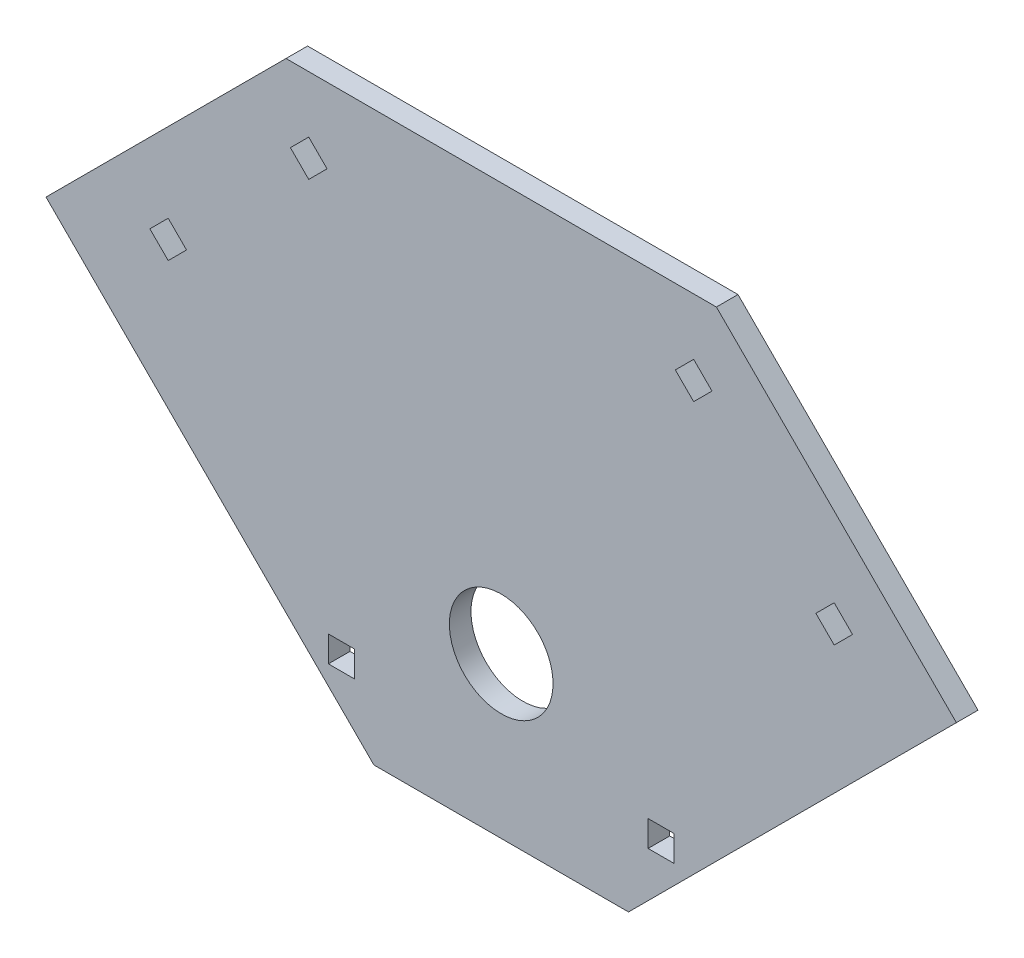
SolidWorks part; units mm, degrees
material "ABS"
ref_plane "Front Plane" through (0, 0, 0) normal (0, 0, 1) x (1, 0, 0)
ref_plane "Top Plane" through (0, 0, 0) normal (0, 1, 0) x (1, 0, 0)
ref_plane "Right Plane" through (0, 0, 0) normal (1, 0, 0) x (0, 0, -1)
sketch "Sketch3" plane through (0, 0, 0) normal (0, 0, 1) x (1, 0, 0)
  line L8 (0, 0) -> (136.4293, 136.4293) construction
  line L9 (0, 0) -> (0, 136.4293) construction
  line L10 (0, 0) -> (-136.4293, 136.4293) construction
  line L20 (-15.2843, -13) -> (15.2843, -13) construction
  line L23 (-15.2843, -13) -> (-77.7817, 49.4975) construction
  line L25 (15.2843, -13) -> (77.7817, 49.4975) construction
  line L27 (-77.7817, 49.4975) -> (-49.4975, 77.7817)
  line L29 (49.4975, 77.7817) -> (77.7817, 49.4975)
  line L32 (-15.2843, -13) -> (15.2843, -13) construction
  line L34 (-27.4975, -22) -> (27.4975, -22)
  line L36 (-27.4975, -22) -> (-88.3883, 38.8909)
  line L37 (-88.3883, 38.8909) -> (-77.7817, 49.4975)
  line L42 (-49.4975, 77.7817) -> (-40.0115, 68.2957) construction
  line L47 (27.4975, -22) -> (88.3883, 38.8909)
  line L48 (88.3883, 38.8909) -> (77.7817, 49.4975)
  line L49 (0, 0) -> (0, -22) construction
  line L50 (-49.4975, 77.7817) -> (-43.8406, 83.4386)
  line L51 (-43.8406, 83.4386) -> (43.8406, 83.4386)
  line L52 (43.8406, 83.4386) -> (49.4975, 77.7817)
  line L53 (49.4975, 77.7817) -> (23.1501, 51.4344) construction
  line L54 (-43.8406, 83.4386) -> (-20.3266, 59.9246) construction
  line L55 (43.8406, 83.4386) -> (35.6049, 75.2028) construction
  line L56 (-81.3173, 44.5477) -> (-77.0746, 48.7904)
  line L57 (-77.0746, 48.7904) -> (-72.832, 44.5477)
  line L58 (-72.832, 44.5477) -> (-77.0746, 40.3051)
  line L59 (-77.0746, 40.3051) -> (-81.3173, 44.5477)
  line L60 (-48.7904, 77.0746) -> (-44.5477, 81.3173)
  line L61 (-44.5477, 81.3173) -> (-40.3051, 77.0746)
  line L62 (-40.3051, 77.0746) -> (-44.5477, 72.832)
  line L63 (-44.5477, 72.832) -> (-48.7904, 77.0746)
  line L64 (40.3051, 77.0746) -> (44.5477, 72.832)
  line L71 (44.5477, 72.832) -> (48.7904, 77.0746)
  line L72 (48.7904, 77.0746) -> (44.5477, 81.3173)
  line L73 (44.5477, 81.3173) -> (40.3051, 77.0746)
  line L74 (72.832, 44.5477) -> (77.0746, 40.3051)
  line L75 (77.0746, 40.3051) -> (81.3173, 44.5477)
  line L76 (81.3173, 44.5477) -> (77.0746, 48.7904)
  line L77 (77.0746, 48.7904) -> (72.832, 44.5477)
  line L82 (0, 0) -> (0, 50) construction
  circle A0 centre (0, 0) radius 12
  point P7 (63.6396, 63.6396)
  point P15 (-63.6396, 63.6396)
  dimension "crankshaftBearingOD" = 24
  dimension "D8" = 45
  dimension "D10" = 45
  dimension "D2" = 90
  dimension "D3" = 90
  dimension "D4" = 40
  dimension "D5" = 40
  dimension "D6" = 13
  dimension "D7" = 22
  dimension "D9" = 8
  dimension "D11" = 15
  dimension "D15" = 1
  dimension "D16" = 6
  dimension "D18" = 1
  dimension "D19" = 6
  dimension "D12" = 176.7767
  dimension "D13" = 105.4386
  dimension "D17" = 50
extrude "Boss-Extrude1" add sketch "Sketch3" along normal blind 5
sketch "Sketch5" plane through (0, 0, 5) normal (0, 0, 1) x (1, 0, 0)
  line L24 (-43.8406, 83.4386) -> (-88.3883, 38.8909)
  line L25 (-88.3883, 38.8909) -> (-27.4975, -22)
  line L26 (-27.4975, -22) -> (27.4975, -22)
  line L27 (27.4975, -22) -> (88.3883, 38.8909)
  line L28 (88.3883, 38.8909) -> (43.8406, 83.4386)
  line L29 (43.8406, 83.4386) -> (-43.8406, 83.4386)
  line L30 (-43.8406, 83.4386) -> (-88.3883, 38.8909)
  line L31 (-88.3883, 38.8909) -> (-27.4975, -22)
  line L32 (-27.4975, -22) -> (27.4975, -22)
  line L33 (27.4975, -22) -> (88.3883, 38.8909)
  line L34 (88.3883, 38.8909) -> (43.8406, 83.4386)
  line L35 (43.8406, 83.4386) -> (-43.8406, 83.4386)
  line L36 (-105.3589, 38.8909) -> (-49.8112, 94.4386)
  line L37 (-49.8112, 94.4386) -> (49.8112, 94.4386)
  line L38 (49.8112, 94.4386) -> (105.3589, 38.8909)
  line L39 (105.3589, 38.8909) -> (29.468, -37)
  line L40 (29.468, -37) -> (-29.468, -37)
  line L41 (-29.468, -37) -> (-105.3589, 38.8909)
  dimension "D2" = 11
  dimension "D3" = 15
  dimension "D4" = 12
  dimension "D5" = 12
  dimension "D6" = 12
  dimension "D7" = 12
  dimension "D1" = 0
extrude "Boss-Extrude2" add sketch "Sketch5" against normal up to surface (5 mm away) up to face at (0, 33.4432, 0)
sketch "Sketch6" plane through (0, 0, 5) normal (0, 0, 1) x (1, 0, 0)
  line L0 (-42.468, -24) -> (42.468, -24) construction
  line L1 (-40, -22) -> (-34, -22)
  line L2 (-40, -22) -> (-40, -16)
  line L3 (-40, -16) -> (-34, -16)
  line L4 (-34, -22) -> (-34, -16)
  line L5 (-40, -22) -> (-34, -16) construction
  line L6 (-40, -16) -> (-34, -22) construction
  line L7 (34, -22) -> (40, -22)
  line L8 (34, -22) -> (34, -16)
  line L9 (34, -16) -> (40, -16)
  line L10 (40, -22) -> (40, -16)
  line L11 (34, -22) -> (40, -16) construction
  line L12 (34, -16) -> (40, -22) construction
  line L13 (-105.3589, 38.8909) -> (-29.468, -37) construction
  line L14 (29.468, -37) -> (105.3589, 38.8909) construction
  line L16 (-48.7904, 77.0746) -> (-77.0746, 48.7904) construction
  line L17 (-77.0746, 48.7904) -> (-62.9325, 62.9325) construction
  line L18 (-62.9325, 62.9325) -> (0, 0) construction
  point P0 (-37, -19)
  point P5 (37, -19)
  dimension "D1" = 6
  dimension "D2" = 24
  dimension "D3" = 2
  dimension "D4" = 2
  dimension "D5" = 37
  dimension "D6" = 37
extrude "Cut-Extrude1" cut sketch "Sketch6" against normal up to surface (5 mm away) up to face at (12, 0, 0)
equation "\"crankshaftBearingOD@Sketch3\"=24.00mm"
